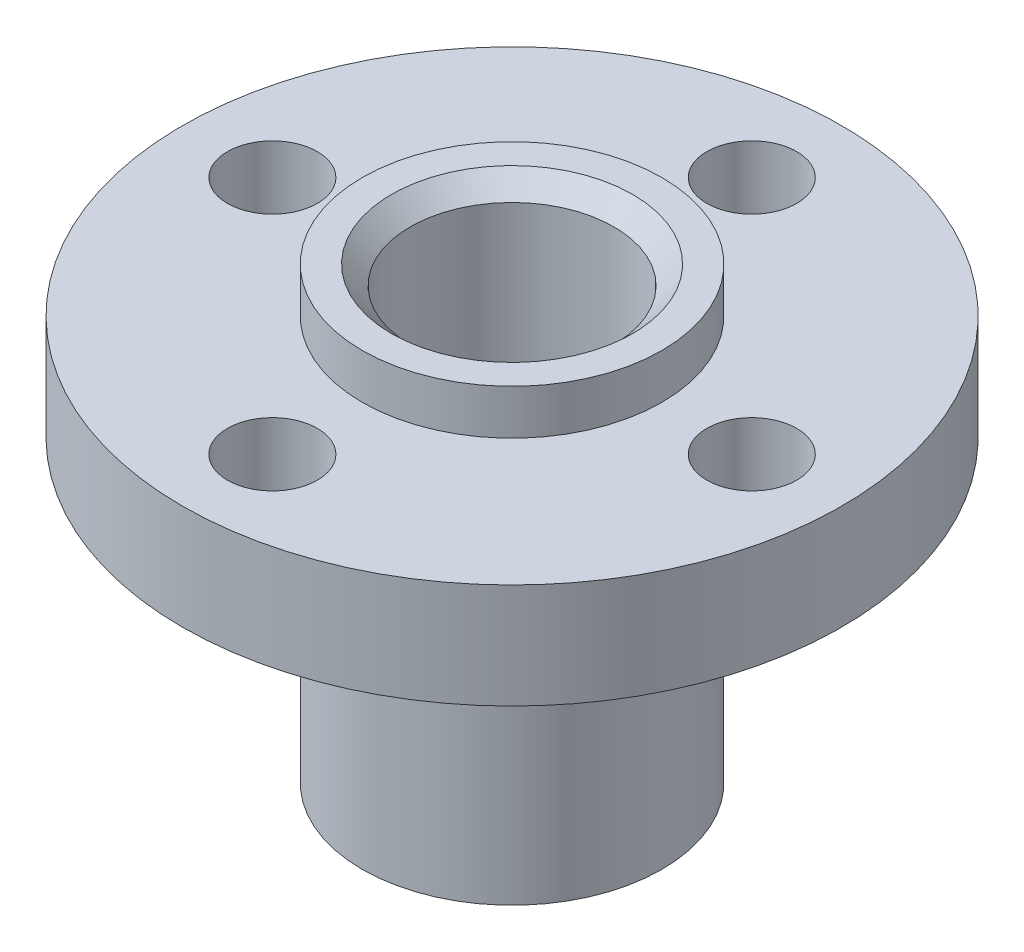
SolidWorks part; units mm, degrees
ref_plane "前视基准面" through (0, 0, 0) normal (0, 0, 1) x (1, 0, 0)
ref_plane "上视基准面" through (0, 0, 0) normal (0, 1, 0) x (1, 0, 0)
ref_plane "右视基准面" through (0, 0, 0) normal (1, 0, 0) x (0, 0, -1)
sketch "草图1" plane through (0, 0, 0) normal (0, 1, 0) x (1, 0, 0)
  circle A0 centre (0, 0) radius 5
  dimension "D1" = 10
extrude "凸台-拉伸2" add sketch "草图1" along normal blind 5 and the other way blind 10
sketch "草图2" plane through (0, 0, 0) normal (0, 1, 0) x (1, 0, 0)
  circle A0 centre (0, 0) radius 11
  circle A1 centre (8, 0) radius 1.5
  circle A2 centre (0, 8) radius 1.5
  circle A3 centre (-8, 0) radius 1.5
  circle A4 centre (0, -8) radius 1.5
  dimension "D1" = 22
  dimension "D2" = 3
  dimension "D3" = 3
  dimension "D4" = 3
  dimension "D5" = 3
  dimension "D6" = 8
  dimension "D7" = 8
  dimension "D8" = 8
  dimension "D9" = 8
extrude "凸台-拉伸3" add sketch "草图2" along normal blind 3.5
hole_wizard "M8 螺纹孔1" positions "草图3" profile "草图4" tap size "M8" standard "GB"
sketch "草图3" plane through (0, 5, 0) normal (0, 1, 0) x (1, 0, 0)
  point P0 (0, 0)
  point P3 (0, 0)
sketch "草图4" plane through (0, 5, 0) normal (1, 0, 0) x (0, 0, 1)
  line L0 (0, 0) -> (0, 24.2929)
  line L1 (0, 24.2929) -> (3.4, 22.25)
  line L2 (3.4, 22.25) -> (3.4, 0.625)
  line L3 (3.4, 0.625) -> (4.025, 0)
  line L5 (4.025, 0) -> (0, 0)
  line L6 (-3.4, 0.625) -> (-4.025, 0) construction
  line L10 (0, 24.2929) -> (-3.4, 22.25) construction
  line L11 (0, -6.35) -> (0, 107.95) construction
  dimension "螺纹孔钻头直径" = 6.8
  dimension "螺纹孔钻头深度" = 22.25
  dimension "近端锥形沉头孔直径" = 8.05
  dimension "近端锥形沉头孔角度" = 90
  dimension "导头角度" = 118
cosmetic thread "孔螺蚊线2" parameters "D1"=15, "D2"=8
